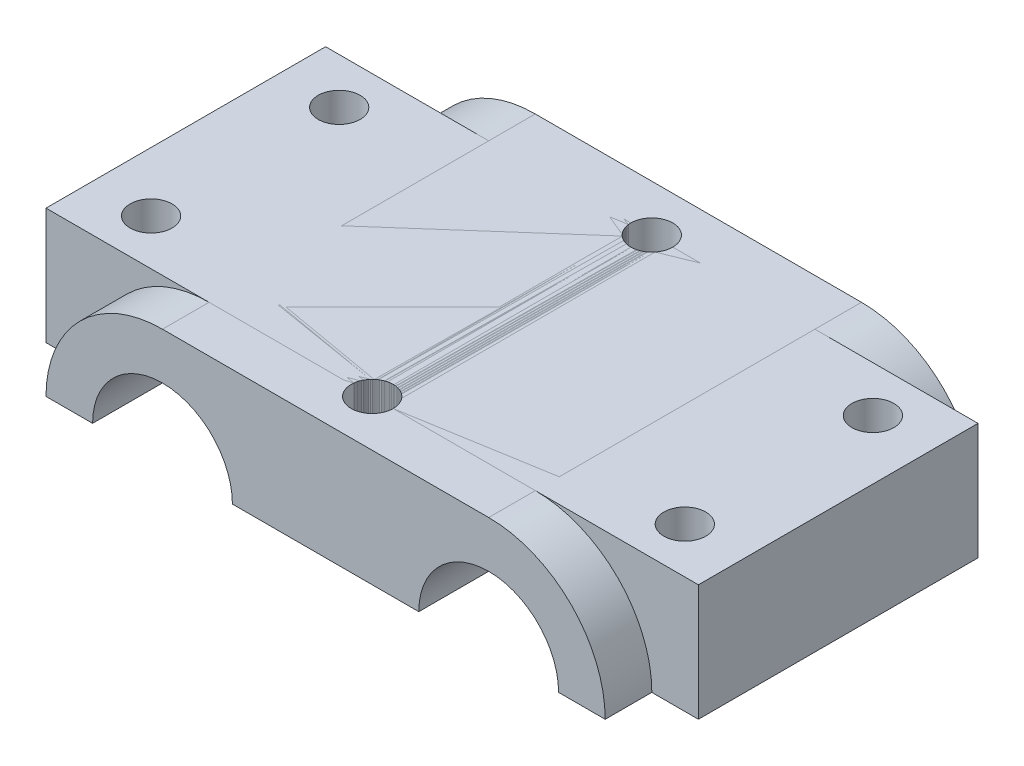
SolidWorks part; units mm, degrees
ref_plane "Front Plane" through (0, 0, 0) normal (0, 0, 1) x (1, 0, 0)
ref_plane "Top Plane" through (0, 0, 0) normal (0, 1, 0) x (1, 0, 0)
ref_plane "Right Plane" through (0, 0, 0) normal (1, 0, 0) x (0, 0, -1)
sketch "Sketch1" plane through (0, 0, 0) normal (0, 0, 1) x (1, 0, 0)
  line L0 (0, 0) -> (0, 14.0967) construction
  line L1 (-10, -6.25) -> (10, -6.25)
  line L2 (-35, -6.25) -> (-25, -6.25)
  line L3 (-35, -6.25) -> (-35, 6.25)
  line L4 (-35, 6.25) -> (35, 6.25)
  line L5 (35, -6.25) -> (35, 6.25)
  line L6 (-35, -6.25) -> (35, 6.25) construction
  line L7 (-35, 6.25) -> (35, -6.25) construction
  line L8 (25, -6.25) -> (35, -6.25)
  arc A0 (-10, -6.25) -> (-25, -6.25) centre (-17.5, -6.25) ccw
  arc A1 (10, -6.25) -> (25, -6.25) centre (17.5, -6.25) cw
  dimension "D3" = 15
  dimension "D1" = 70
  dimension "D2" = 12.5
extrude "Boss-Extrude1" add sketch "Sketch1" along normal blind 30
sketch "Sketch2" plane through (0, 0, 30) normal (0, 0, 1) x (1, 0, 0)
  line L0 (0, 6.25) -> (0, -6.25) construction
  line L1 (35, 6.25) -> (-35, 6.25) construction
  line L2 (-10, -6.25) -> (10, -6.25) construction
  line L3 (-35, -6.25) -> (-25, -6.25) construction
  line L4 (-25, -6.25) -> (-30, -6.25)
  line L5 (-17.5, 6.25) -> (17.5, 6.25)
  line L6 (-10, -6.25) -> (10, -6.25)
  line L7 (25, -6.25) -> (30, -6.25)
  arc A0 (-17.5, 6.25) -> (-30, -6.25) centre (-17.5, -6.25) ccw
  arc A2 (-25, -6.25) -> (-10, -6.25) centre (-17.5, -6.25) cw
  arc A3 (25, -6.25) -> (10, -6.25) centre (17.5, -6.25) ccw
  arc A4 (17.5, 6.25) -> (30, -6.25) centre (17.5, -6.25) cw
  point P12 (-26.3388, 2.5888)
  dimension "D2" = 12.5
  dimension "D1" = 12.5
extrude "Boss-Extrude2" add sketch "Sketch2" along normal blind 5 and the other way blind 35 separate body
sketch "Sketch3" plane through (0, 6.25, 0) normal (0, 1, 0) x (1, 0, 0)
  line L0 (0, 0) -> (0, -15) construction
  line L1 (0, -15) -> (-35, -15) construction
  line L2 (-35, -30) -> (-35, 0) construction
  circle A0 centre (0, 0) radius 2.25
  circle A1 centre (-28.6331, -4.9089) radius 2.25
  circle A2 centre (28.6331, -4.9089) radius 2.25
  circle A3 centre (28.6331, -25.0911) radius 2.25
  circle A4 centre (0, -30) radius 2.25
  circle A5 centre (-28.6331, -25.0911) radius 2.25
  point P9 (0, 0)
  point P10 (0, 0)
  point P11 (0, 0)
  dimension "D1" = 4.5
  dimension "D2" = 4.5
extrude "Cut-Extrude1" cut sketch "Sketch3" against normal through all
